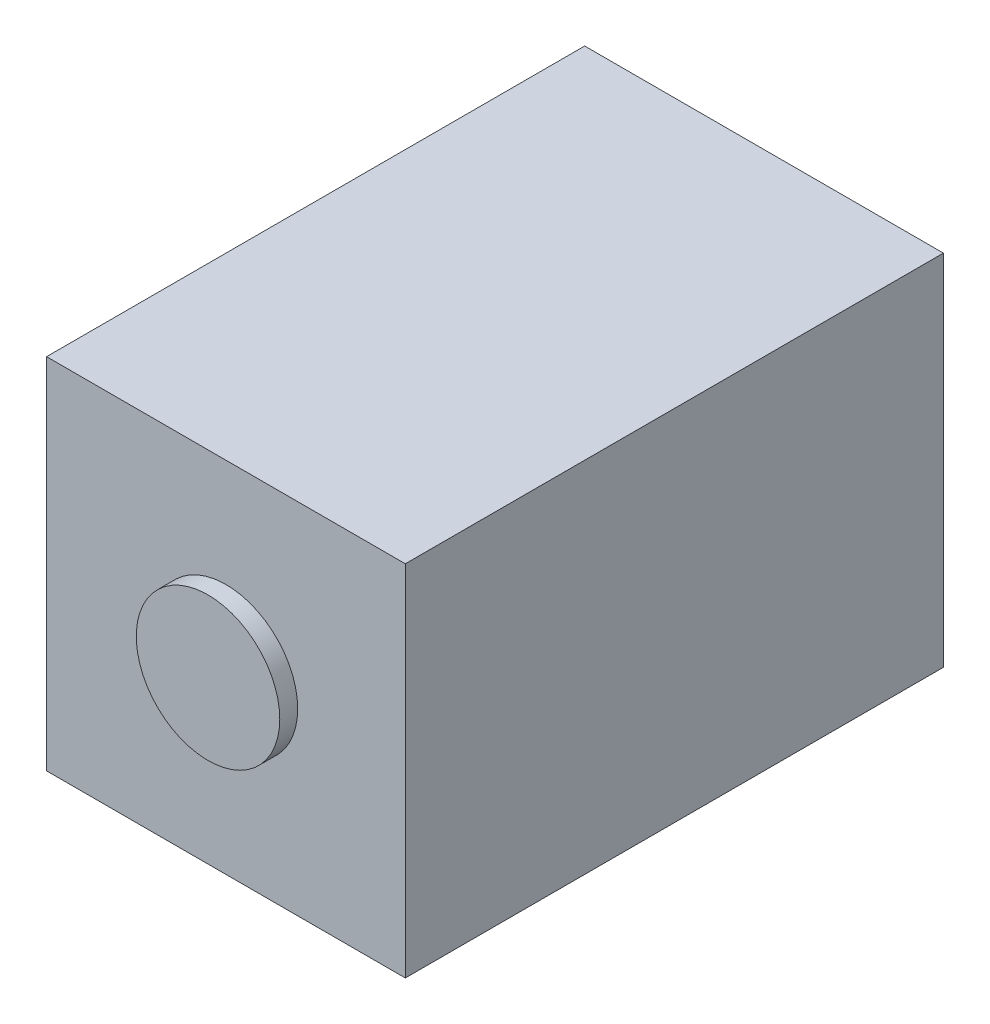
SolidWorks part; units mm, degrees
ref_plane "前视基准面" through (0, 0, 0) normal (0, 0, 1) x (1, 0, 0)
ref_plane "上视基准面" through (0, 0, 0) normal (0, 1, 0) x (1, 0, 0)
ref_plane "右视基准面" through (0, 0, 0) normal (1, 0, 0) x (0, 0, -1)
other "Configuration Table"
sketch "草图1" plane through (0, 0, 0) normal (0, 0, 1) x (1, 0, 0)
  line L1 (-100, -100) -> (100, -100)
  line L2 (-100, -100) -> (-100, 100)
  line L3 (-100, 100) -> (100, 100)
  line L4 (100, -100) -> (100, 100)
  line L5 (-100, -100) -> (100, 100) construction
  line L6 (-100, 100) -> (100, -100) construction
  point P0 (0, 0)
  dimension "D1" = 200
extrude "凸台-拉伸1" add sketch "草图1" along normal mid plane 300
sketch "草图2" plane through (0, 0, 150) normal (0, 0, 1) x (1, 0, 0)
  circle A0 centre (0, 0) radius 40
  dimension "D1" = 80
extrude "凸台-拉伸2" add sketch "草图2" along normal blind 10
sketch "草图3" plane through (0, 0, -150) normal (0, 0, -1) x (-1, 0, 0)
  circle A0 centre (0, 0) radius 40
  dimension "D1" = 80
extrude "凸台-拉伸3" add sketch "草图3" along normal blind 10
